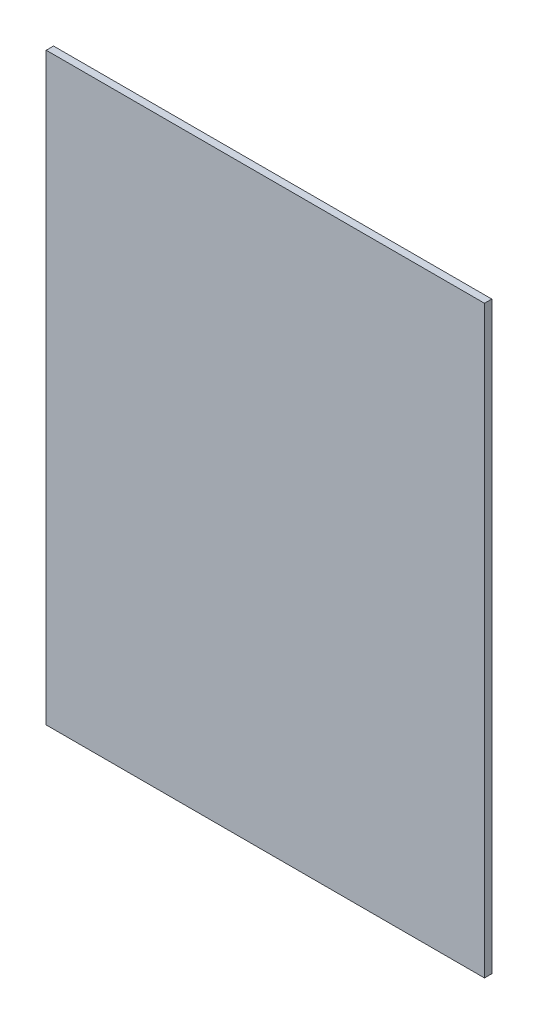
SolidWorks part; units mm, degrees
ref_plane "Plan de face" through (0, 0, 0) normal (0, 0, 1) x (1, 0, 0)
ref_plane "Plan de dessus" through (0, 0, 0) normal (0, 1, 0) x (1, 0, 0)
ref_plane "Plan de droite" through (0, 0, 0) normal (1, 0, 0) x (0, 0, -1)
sketch "Esquisse1" plane through (0, 0, 0) normal (0, 0, 1) x (1, 0, 0)
  line L1 (-250, 400) -> (350, 400)
  line L2 (-250, 400) -> (-250, -400)
  line L3 (-250, -400) -> (350, -400)
  line L4 (350, 400) -> (350, -400)
  point P7 (-144.364, -42.7842)
  dimension "D1" = 600
  dimension "D2" = 800
  dimension "D3" = 400
  dimension "D4" = 250
extrude "Boss.-Extru.1" add sketch "Esquisse1" along normal blind 10
